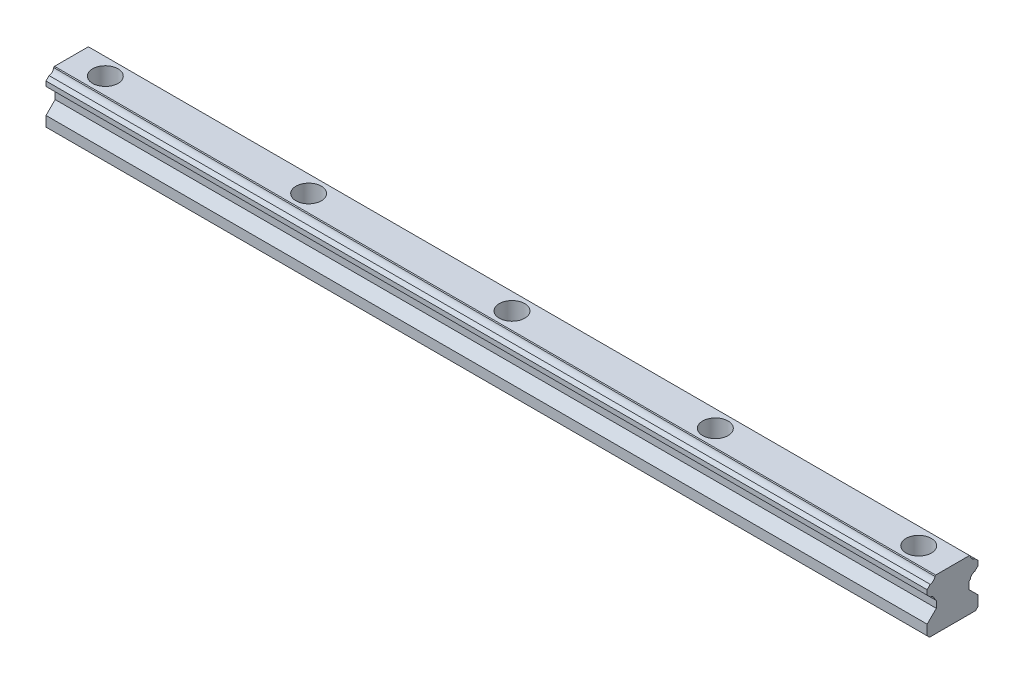
SolidWorks part; units mm, degrees
material "201 Отожженная нержавеющая сталь (SS)"
ref_plane "Спереди" through (0, 0, 0) normal (0, 0, 1) x (1, 0, 0)
ref_plane "Сверху" through (0, 0, 0) normal (0, 1, 0) x (1, 0, 0)
ref_plane "Сбоку" through (0, 0, 0) normal (1, 0, 0) x (0, 0, -1)
sketch "Эскиз1" plane through (0, 0, 0) normal (1, 0, 0) x (0, 0, -1)
  line L0 (-7.5, 0.7071) -> (-6.7929, 0)
  line L1 (-6.7929, 0) -> (6.7929, 0)
  line L2 (6.7929, 0) -> (7.5, 0.7071)
  line L3 (7.5, 0.7071) -> (7.5, 3.7)
  line L4 (7.5, 3.7) -> (4.8, 6.4)
  line L5 (4.8, 6.4) -> (4.8, 8.4)
  line L6 (4.8, 8.4) -> (5.2144, 8.8144)
  line L7 (6.5856, 10.1856) -> (7.5, 11.1)
  line L8 (7.5, 11.1) -> (7.5, 12.5)
  line L9 (7.5, 12.5) -> (6.5856, 13.4144)
  line L10 (5.2144, 14.7856) -> (5, 15)
  line L11 (5, 15) -> (-5, 15)
  line L12 (-5, 15) -> (-5.2144, 14.7856)
  line L13 (-6.5856, 13.4144) -> (-7.5, 12.5)
  line L14 (-7.5, 12.5) -> (-7.5, 11.1)
  line L15 (-7.5, 11.1) -> (-6.5856, 10.1856)
  line L16 (-5.2144, 8.8144) -> (-4.8, 8.4)
  line L17 (-4.8, 8.4) -> (-4.8, 6.4)
  line L18 (-4.8, 6.4) -> (-7.5, 3.7)
  line L19 (-7.5, 3.7) -> (-7.5, 0.7071)
  arc A0 (5.2144, 8.8144) -> (6.5856, 10.1856) centre (6.8, 8.6) cw
  arc A1 (6.5856, 13.4144) -> (5.2144, 14.7856) centre (6.8, 15) cw
  arc A2 (-5.2144, 14.7856) -> (-6.5856, 13.4144) centre (-6.8, 15) cw
  arc A3 (-6.5856, 10.1856) -> (-5.2144, 8.8144) centre (-6.8, 8.6) cw
  dimension "D1" = 15
  dimension "D2" = 15
  dimension "D3" = 7.5
extrude "Бобышка-Вытянуть1" add sketch "Эскиз1" against normal mid plane 260
hole_wizard "Цековка M4 для болта с шестигранной головкой класса А ГОСТ 78051" positions "Эскиз3" profile "Эскиз2" counterbore size "M4" standard "ГОСТ" end condition through all
sketch "Эскиз3" plane through (0, 15, 0) normal (0, 1, 0) x (1, 0, 0)
  point P0 (0, 0)
sketch "Эскиз2" plane through (0, 15, 0) normal (1, 0, 0) x (0, 0, 1)
  line L0 (0, 0) -> (0, 15)
  line L1 (0, 15) -> (2.25, 15)
  line L3 (2.25, 15) -> (2.25, 5.3)
  line L4 (2.25, 5.3) -> (3.75, 5.3)
  line L5 (3.75, 5.3) -> (3.75, 0)
  line L7 (3.75, 0) -> (0, 0)
  line L11 (0, -6.35) -> (0, 107.95) construction
  dimension "Диаметр сквозного отверстия" = 4.5
  dimension "Глубина сквозного отверстия" = 15
  dimension "Диаметр цековки" = 7.5
  dimension "Глубина цековки" = 5.3
pattern_linear "Линейный массив1" count 3 spacing 60 along (1, 0, 0) of "Цековка M4 для болта с шестигранной головкой класса А ГОСТ 78051"
pattern_linear "Линейный массив2" count 3 spacing 60 along (-1, 0, 0) of "Цековка M4 для болта с шестигранной головкой класса А ГОСТ 78051"
